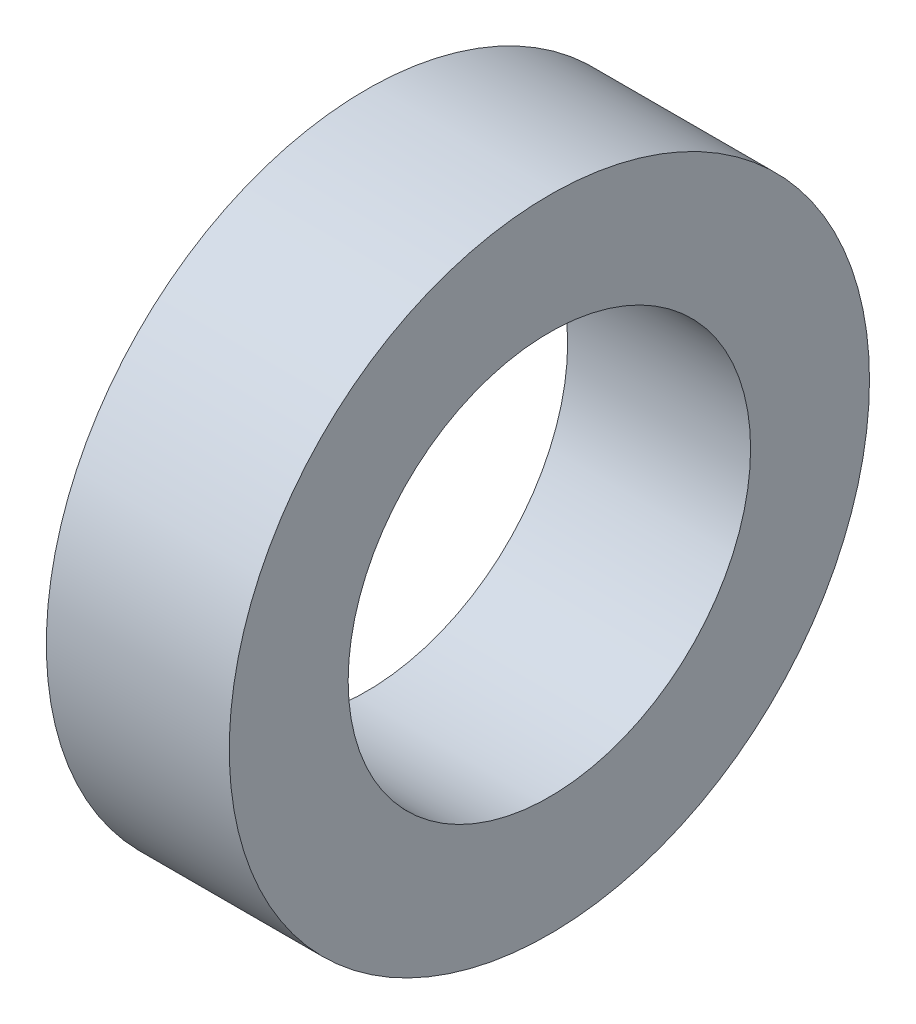
SolidWorks part; units mm, degrees
ref_plane "Front Plane" through (0, 0, 0) normal (0, 0, 1) x (1, 0, 0)
ref_plane "Top Plane" through (0, 0, 0) normal (0, 1, 0) x (1, 0, 0)
ref_plane "Right Plane" through (0, 0, 0) normal (1, 0, 0) x (0, 0, -1)
sketch "Sketch1" plane through (0, 0, 0) normal (1, 0, 0) x (0, 0, -1)
  circle A0 centre (0, 0) radius 2.794
  circle A1 centre (0, 0) radius 4.445
  dimension "D1" = 5.588
  dimension "D2" = 8.89
extrude "Boss-Extrude1" add sketch "Sketch1" along normal blind 2.54 contours A1 A0
